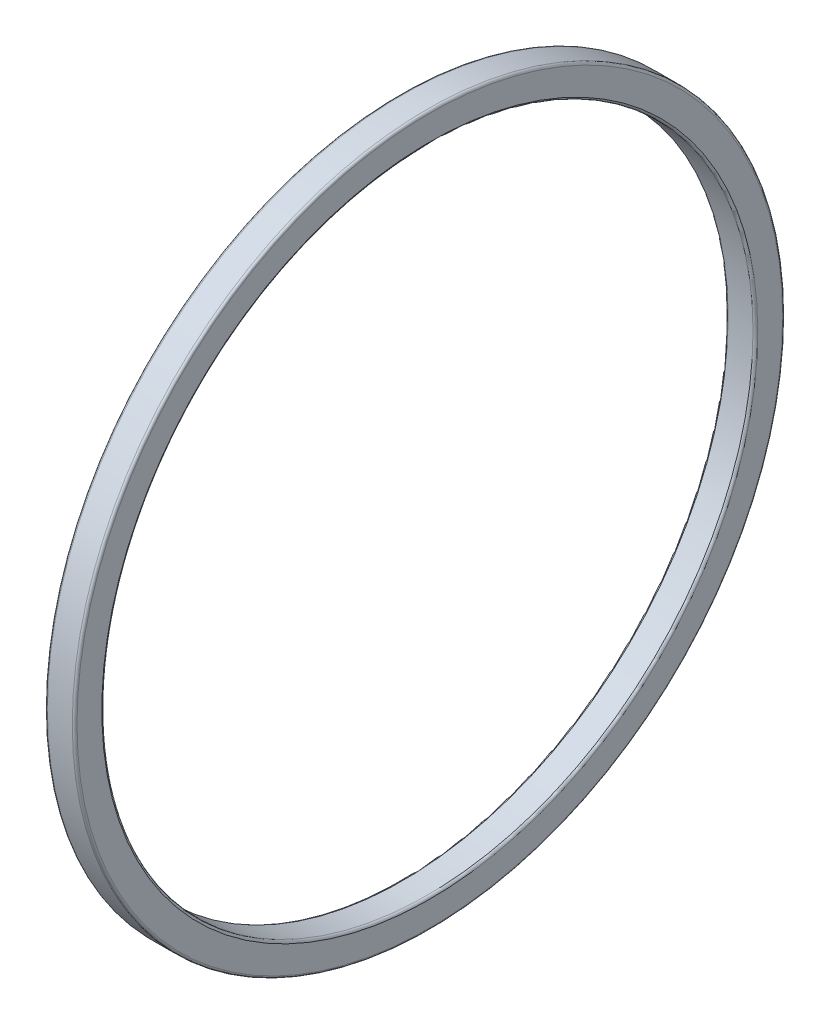
SolidWorks part; units mm, degrees
material "6061-T6 (SS)"
ref_plane "Front Plane" through (0, 0, 0) normal (0, 0, 1) x (1, 0, 0)
ref_plane "Top Plane" through (0, 0, 0) normal (0, 1, 0) x (1, 0, 0)
ref_plane "Right Plane" through (0, 0, 0) normal (1, 0, 0) x (0, 0, -1)
sketch "Sketch1" plane through (0, 0, 0) normal (1, 0, 0) x (0, 0, -1)
  circle A0 centre (0, 0) radius 69.85
  circle A1 centre (0, 0) radius 76.2
  dimension "D1" = 139.7
  dimension "D2" = 152.4
extrude "Boss-Extrude1" add sketch "Sketch1" along normal mid plane 6.35
fillet "Fillet1" radius 0.508 4 edges at (-3.175, 0, -69.85) (-3.175, 0, -76.2) (3.175, 0, -69.85) (3.175, 0, -76.2)
